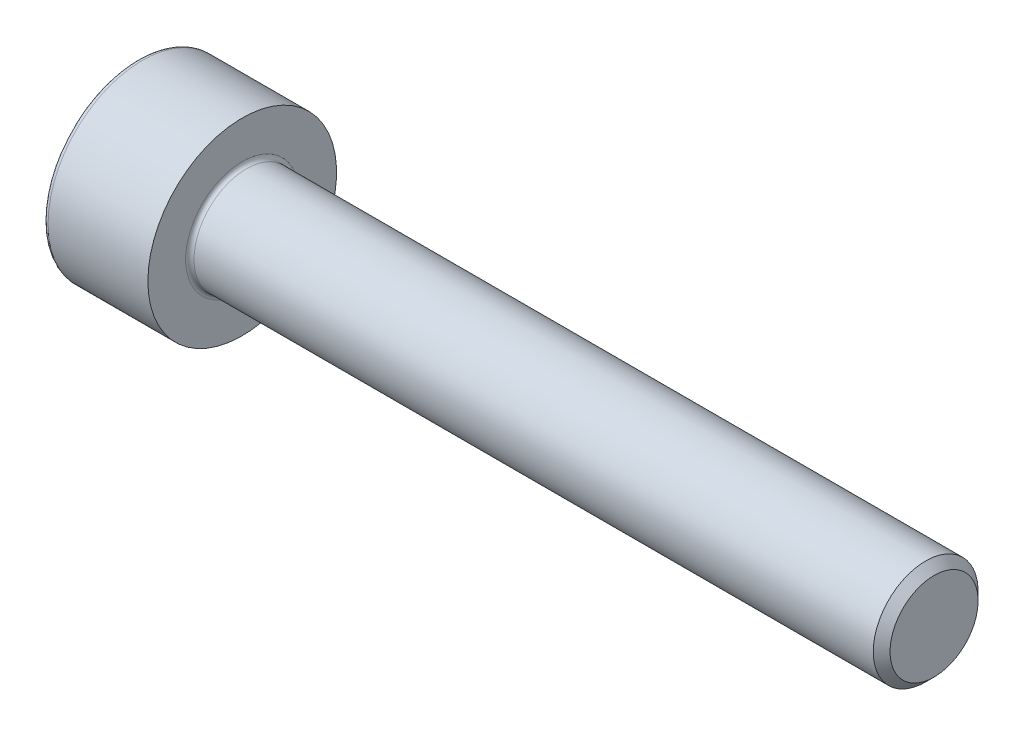
SolidWorks part; units mm, degrees
ref_plane "Front Plane" through (0, 0, 0) normal (0, 0, 1) x (1, 0, 0)
ref_plane "Top Plane" through (0, 0, 0) normal (0, 1, 0) x (1, 0, 0)
ref_plane "Right Plane" through (0, 0, 0) normal (1, 0, 0) x (0, 0, -1)
sketch "Sketch1" plane through (0, 0, 0) normal (0, 0, 1) x (1, 0, 0)
  line L0 (0, 0) -> (0, 2.25)
  line L1 (0, 2.25) -> (2.5, 2.25)
  line L2 (2.5, 2.25) -> (2.5, 0)
  line L3 (0, 0) -> (4.2799, 0) construction
  line L4 (2.5, 0) -> (19, 0)
  line L5 (19, 0) -> (19, 1.25)
  line L6 (19, 1.25) -> (2.5, 1.25)
  dimension "D1" = 16.5
revolve "Revolve1" add sketch "Sketch1" angle 360 about L3
fillet "Fillet1" radius 0.1 1 edges at (2.5, 0, 1.25)
fillet "Fillet2" radius 0.12 1 edges at (0, 0, 2.25)
chamfer "Chamfer1" distance 0.2 angle 45 1 edges at (19, 0, 1.25)
sketch "Sketch2" plane through (0, 0, 0) normal (-1, 0, 0) x (0, 0, 1)
  line L1 (0, 1.1547) -> (-1, 0.5774)
  line L2 (-1, 0.5774) -> (-1, -0.5774)
  line L3 (-1, -0.5774) -> (0, -1.1547)
  line L4 (0, -1.1547) -> (1, -0.5774)
  line L5 (1, -0.5774) -> (1, 0.5774)
  line L6 (1, 0.5774) -> (0, 1.1547)
  circle A0 centre (0, 0) radius 1 construction
extrude "Extrude1" cut sketch "Sketch2" against normal blind 1
